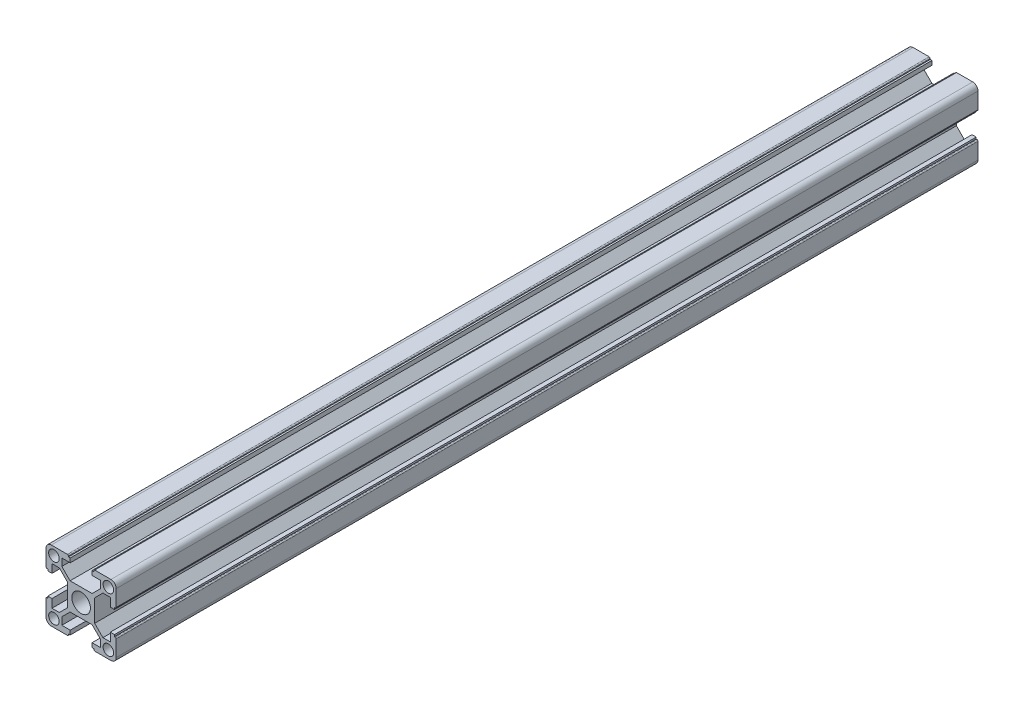
SolidWorks part; units mm, degrees
ref_plane "前视基准面" through (0, 0, 0) normal (0, 0, 1) x (1, 0, 0)
ref_plane "上视基准面" through (0, 0, 0) normal (0, 1, 0) x (1, 0, 0)
ref_plane "右视基准面" through (0, 0, 0) normal (1, 0, 0) x (0, 0, -1)
sketch "草图1" plane through (0, 0, 0) normal (0, 0, 1) x (1, 0, 0)
  line L0 (-7.75, 0) -> (0, 0) construction
  line L1 (7.75, -7.75) -> (-7.75, -7.75) construction
  line L2 (7.75, -7.75) -> (7.75, 7.75) construction
  line L3 (7.75, 7.75) -> (-7.75, 7.75) construction
  line L4 (-7.75, -7.75) -> (-7.75, 7.75) construction
  line L5 (7.75, -7.75) -> (-7.75, 7.75) construction
  line L6 (7.75, 7.75) -> (-7.75, -7.75) construction
  line L7 (0, 0) -> (0, 7.75) construction
  line L8 (3.1429, 3.85) -> (-3.1429, 3.85)
  line L9 (-3.1429, 3.85) -> (-5.5, 6.2071)
  line L10 (-5.5, 6.2071) -> (-5.5, 8.3)
  line L11 (-5.5, 8.3) -> (-3.1, 8.3)
  line L12 (-3.1, 8.3) -> (-3.1, 9.5)
  line L13 (-3.1, 9.5) -> (-3.6, 9.5)
  line L14 (-3.6, 9.5) -> (-3.6, 9.7)
  line L15 (-3.9, 10) -> (-8.5, 10)
  line L16 (-3.85, -3.1429) -> (-3.85, 3.1429)
  line L17 (-3.85, 3.1429) -> (-6.2071, 5.5)
  line L18 (-6.2071, 5.5) -> (-8.3, 5.5)
  line L19 (-8.3, 5.5) -> (-8.3, 3.1)
  line L20 (-9.5, 3.1) -> (-9.5, 3.6)
  line L21 (-8.3, 3.1) -> (-9.5, 3.1)
  line L22 (-9.5, 3.6) -> (-9.7, 3.6)
  line L23 (-10, 3.9) -> (-10, 8.5)
  line L24 (5.5, 8.3) -> (3.1, 8.3)
  line L25 (3.6, 9.5) -> (3.6, 9.7)
  line L26 (3.1, 9.5) -> (3.6, 9.5)
  line L27 (3.1, 8.3) -> (3.1, 9.5)
  line L28 (5.5, 6.2071) -> (5.5, 8.3)
  line L29 (3.1429, 3.85) -> (5.5, 6.2071)
  line L30 (3.85, -3.1429) -> (3.85, 3.1429)
  line L31 (3.85, 3.1429) -> (6.2071, 5.5)
  line L32 (9.5, 3.6) -> (9.7, 3.6)
  line L33 (8.3, 3.1) -> (9.5, 3.1)
  line L34 (9.5, 3.1) -> (9.5, 3.6)
  line L35 (8.3, 5.5) -> (8.3, 3.1)
  line L36 (6.2071, 5.5) -> (8.3, 5.5)
  line L37 (10, 3.9) -> (10, 8.5)
  line L38 (3.9, 10) -> (8.5, 10)
  line L39 (-9.5, -3.6) -> (-9.7, -3.6)
  line L40 (-8.3, -3.1) -> (-9.5, -3.1)
  line L41 (-9.5, -3.1) -> (-9.5, -3.6)
  line L42 (-8.3, -5.5) -> (-8.3, -3.1)
  line L43 (-6.2071, -5.5) -> (-8.3, -5.5)
  line L44 (-3.85, -3.1429) -> (-6.2071, -5.5)
  line L45 (-3.1429, -3.85) -> (-5.5, -6.2071)
  line L46 (-5.5, -6.2071) -> (-5.5, -8.3)
  line L47 (-3.6, -9.5) -> (-3.6, -9.7)
  line L48 (-3.1, -9.5) -> (-3.6, -9.5)
  line L49 (-3.1, -8.3) -> (-3.1, -9.5)
  line L50 (-5.5, -8.3) -> (-3.1, -8.3)
  line L51 (5.5, -6.2071) -> (5.5, -8.3)
  line L52 (3.1, -8.3) -> (3.1, -9.5)
  line L53 (3.1, -9.5) -> (3.6, -9.5)
  line L54 (3.6, -9.5) -> (3.6, -9.7)
  line L55 (5.5, -8.3) -> (3.1, -8.3)
  line L56 (3.1429, -3.85) -> (5.5, -6.2071)
  line L57 (3.1429, -3.85) -> (-3.1429, -3.85)
  line L58 (3.85, -3.1429) -> (6.2071, -5.5)
  line L59 (6.2071, -5.5) -> (8.3, -5.5)
  line L60 (8.3, -5.5) -> (8.3, -3.1)
  line L61 (9.5, -3.1) -> (9.5, -3.6)
  line L62 (8.3, -3.1) -> (9.5, -3.1)
  line L63 (9.5, -3.6) -> (9.7, -3.6)
  line L64 (3.9, -10) -> (8.5, -10)
  line L65 (10, -3.9) -> (10, -8.5)
  line L66 (-10, -3.9) -> (-10, -8.5)
  line L67 (-3.9, -10) -> (-8.5, -10)
  circle A0 centre (0, 0) radius 2.65
  circle A1 centre (-7.75, 7.75) radius 1.5
  circle A2 centre (7.75, 7.75) radius 1.5
  circle A3 centre (7.75, -7.75) radius 1.5
  circle A4 centre (-7.75, -7.75) radius 1.5
  arc A5 (-10, -8.5) -> (-8.5, -10) centre (-8.5, -8.5) ccw
  arc A6 (8.5, -10) -> (10, -8.5) centre (8.5, -8.5) ccw
  arc A7 (10, 8.5) -> (8.5, 10) centre (8.5, 8.5) ccw
  arc A8 (-8.5, 10) -> (-10, 8.5) centre (-8.5, 8.5) ccw
  arc A9 (3.6, -9.7) -> (3.9, -10) centre (3.9, -9.7) ccw
  arc A10 (-3.6, -9.7) -> (-3.9, -10) centre (-3.9, -9.7) cw
  arc A11 (-9.7, -3.6) -> (-10, -3.9) centre (-9.7, -3.9) ccw
  arc A12 (9.7, -3.6) -> (10, -3.9) centre (9.7, -3.9) cw
  arc A13 (9.7, 3.6) -> (10, 3.9) centre (9.7, 3.9) ccw
  arc A14 (-9.7, 3.6) -> (-10, 3.9) centre (-9.7, 3.9) cw
  arc A15 (3.6, 9.7) -> (3.9, 10) centre (3.9, 9.7) cw
  arc A16 (-3.6, 9.7) -> (-3.9, 10) centre (-3.9, 9.7) ccw
  point P46 (0, 3.85)
  point P56 (-3.85, 0)
  point P78 (3.85, 0)
  point P87 (-10, -10)
  point P90 (10, -10)
  point P93 (10, 10)
  point P96 (-10, 10)
  point P99 (3.6, -10)
  point P102 (-3.6, -10)
  point P105 (-10, -3.6)
  point P108 (10, -3.6)
  point P111 (10, 3.6)
  point P114 (-10, 3.6)
  point P117 (3.6, 10)
  point P120 (-3.6, 10)
  dimension "D1" = 5.3
  dimension "D2" = 3
  dimension "D11" = 1.5
  dimension "D12" = 2.25
  dimension "D13" = 0.3
  dimension "D3" = 7.7
  dimension "D4" = 6.2
  dimension "D5" = 1.7
  dimension "D6" = 1.2
  dimension "D7" = 20
  dimension "D8" = 7.2
  dimension "D9" = 11
  dimension "D10" = 1
extrude "凸台-拉伸1" add sketch "草图1" along normal mid plane 245.4
sketch "草图2" plane through (0, 0, 0) normal (0, 1, 0) x (1, 0, 0)
  line L0 (3.1429, 122.7) -> (-3.1429, 122.7) construction
  circle A0 centre (0, 112.7) radius 2.1
  circle A1 centre (0, 27.3) radius 2.1
  dimension "D1" = 4.2
  dimension "D2" = 10
  dimension "D3" = 85.4
extrude "切除-拉伸1" cut sketch "草图2" against normal through all both and the other way through all
sketch "草图3" plane through (0, -3.85, 0) normal (0, -1, 0) x (1, 0, 0)
  circle A0 centre (0, -112.7) radius 4.25
  circle A1 centre (0, -27.3) radius 4.25
  dimension "D1" = 8.5
extrude "切除-拉伸2" cut sketch "草图3" along normal through all
sketch "草图4" plane through (-3.85, 0, 0) normal (-1, 0, 0) x (0, 0, 1)
  line L1 (122.7, 3.1429) -> (122.7, -3.1429) construction
  line L2 (122.7, -10) -> (-122.7, -10) construction
  circle A0 centre (112.7, 0) radius 2.1
  dimension "D1" = 10
  dimension "D2" = 4.2
  dimension "D3" = 10
extrude "切除-拉伸3" cut sketch "草图4" against normal through all
